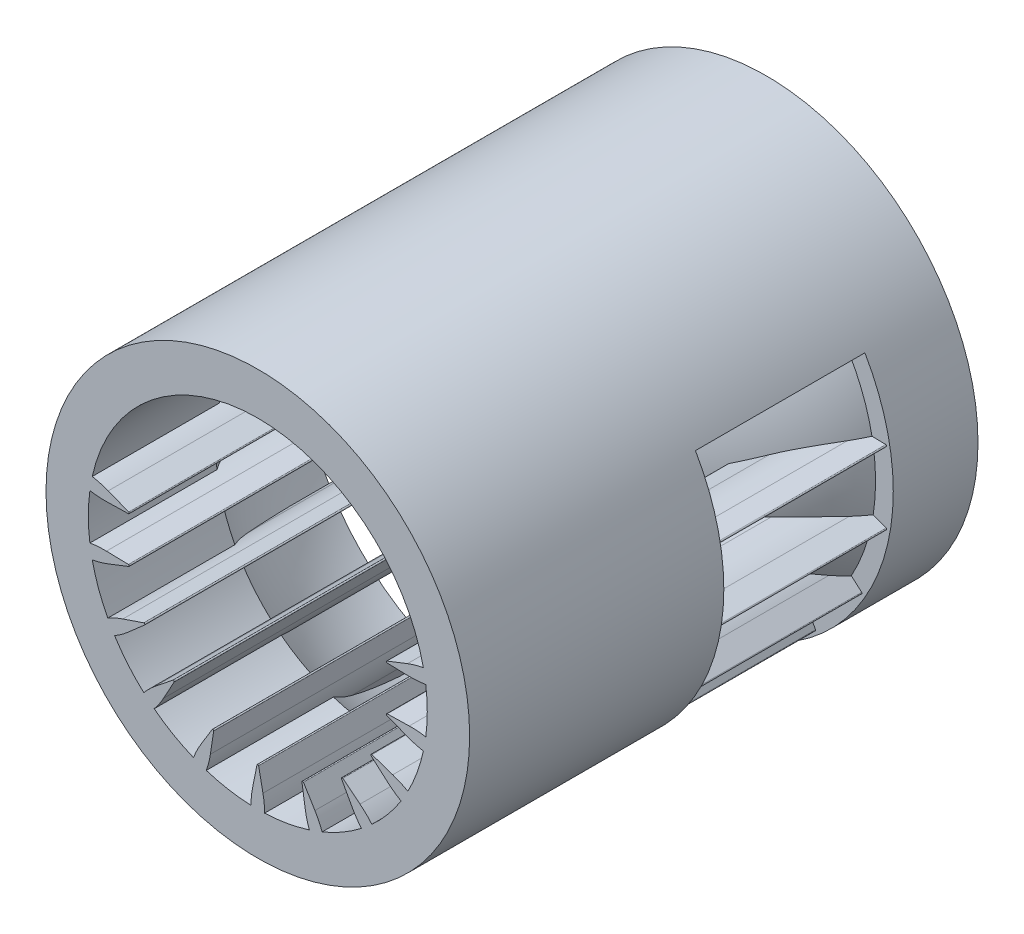
SolidWorks part; units mm, degrees
ref_plane "前视基准面" through (0, 0, 0) normal (0, 0, 1) x (1, 0, 0)
ref_plane "上视基准面" through (0, 0, 0) normal (0, 1, 0) x (1, 0, 0)
ref_plane "右视基准面" through (0, 0, 0) normal (1, 0, 0) x (0, 0, -1)
other "Configuration Table"
sketch "草图1" plane through (0, 0, 0) normal (0, 0, 1) x (1, 0, 0)
  circle A0 centre (0, 0) radius 20
  circle A1 centre (0, 0) radius 25
  dimension "D1" = 40
  dimension "D2" = 50
extrude "凸台-拉伸1" add sketch "草图1" along normal blind 10
sketch "草图2" plane through (0, 0, 10) normal (0, 0, 1) x (1, 0, 0)
  line L0 (0, 0) -> (0, 10.9163) construction
  line L1 (-21.6506, 12.5) -> (-17.3205, 10)
  line L2 (21.6506, 12.5) -> (17.3205, 10)
  arc A0 (21.6506, 12.5) -> (-21.6506, 12.5) centre (0, 0) ccw
  arc A1 (-17.3205, 10) -> (17.3205, 10) centre (0, 0) cw
  circle A3 centre (0, 0) radius 20 construction
  circle A5 centre (0, 0) radius 25 construction
  point P12 (19.7223, 3.3212)
  dimension "D1" = 120
extrude "凸台-拉伸2" add sketch "草图2" along normal blind 50
sketch "草图3" plane through (0, 0, 0) normal (1, 0, 0) x (0, 0, -1)
  line L0 (0, -25) -> (0, 25) construction
  line L1 (-25, 0) -> (-20, 0)
  line L2 (0, -20) -> (0, -25)
  line L3 (-24.8747, -2.5) -> (-19.8431, -2.5)
  line L6 (-45, -20) -> (-60, -20)
  line L7 (-10, 12.5) -> (-10, -25) construction
  line L8 (-10, -25) -> (0, -25) construction
  line L9 (-60, 25) -> (-60, 12.5) construction
  line L10 (-60, -20) -> (-60, -25)
  line L11 (-30, -25) -> (-60, -25)
  arc A0 (0, -25) -> (-25, 0) centre (0, 0) cw
  arc A1 (-20, 0) -> (0, -20) centre (0, 0) ccw
  arc A4 (-45, -20) -> (-30, -25) centre (-30, 0) ccw
  dimension "D1" = 20
  dimension "D3" = 25
  dimension "D2" = 2.5
  dimension "D4" = 20
revolve "旋转1" add sketch "草图3" angle 360 about L1
sketch "草图4" plane through (0, 0, 10) normal (0, 0, 1) x (1, 0, 0)
  line L0 (0, -25) -> (0, -15) construction
  line L1 (-0.0981, -15.4903) -> (-0.6078, -18.0388)
  line L2 (-0.0981, -24.5097) -> (-0.6078, -21.9612)
  line L3 (0.0981, -15.4903) -> (0.6078, -18.0388)
  line L4 (0.0981, -24.5097) -> (0.6078, -21.9612)
  arc A0 (-21.6506, 12.5) -> (21.6506, 12.5) centre (0, 0) ccw construction
  arc A2 (0.6078, -18.0388) -> (0.6078, -21.9612) centre (-9.198, -20) cw
  arc A3 (-0.6078, -18.0388) -> (-0.6078, -21.9612) centre (9.198, -20) ccw
  arc A4 (-0.0981, -15.4903) -> (0.0981, -15.4903) centre (0, -15.5099) cw
  arc A5 (-0.0981, -24.5097) -> (0.0981, -24.5097) centre (0, -24.4901) ccw
  point P7 (0, 0)
  point P10 (4.7053, -23.1803)
  point P13 (1, -20)
  point P16 (-1, -20)
  dimension "D4" = 10
  dimension "D5" = 0.1
  dimension "D1" = 10
  dimension "D2" = 1
  dimension "D3" = 5
extrude "凸台-拉伸3" add sketch "草图4" along normal blind 50
pattern_circular "阵列(圆周)1" count 6 every 20 about axis through (0, 0, 0) along (0, 0, 1) of "凸台-拉伸3"
sketch "草图5" plane through (0, 0, 0) normal (1, 0, 0) x (0, 0, -1)
  line L0 (0, 0) -> (14.2717, 0) construction
  circle A0 centre (0, 0) radius 20
  dimension "D1" = 40
revolve "切除-旋转3" cut sketch "草图5" angle 360 about L0
